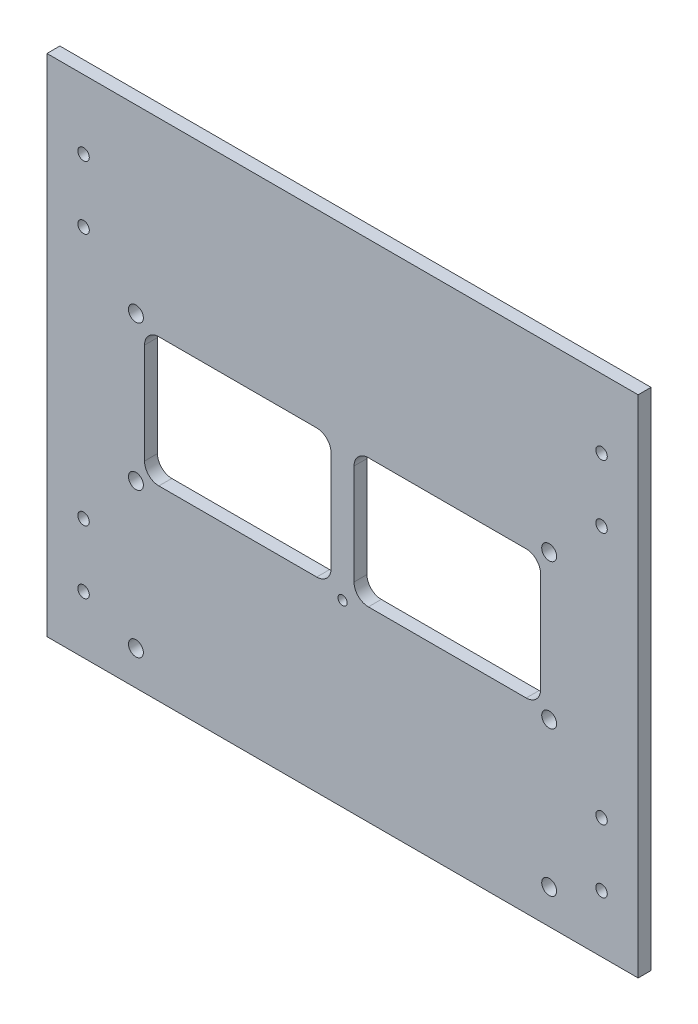
SolidWorks part; units mm, degrees
material "ABS PC"
ref_plane "前视基准面" through (0, 0, 0) normal (0, 0, 1) x (1, 0, 0)
ref_plane "上视基准面" through (0, 0, 0) normal (0, 1, 0) x (1, 0, 0)
ref_plane "右视基准面" through (0, 0, 0) normal (1, 0, 0) x (0, 0, -1)
sketch "草图1" plane through (0, 0, 0) normal (0, 0, 1) x (1, 0, 0)
  line L1 (0, 0) -> (206, 0)
  line L2 (0, 0) -> (0, 176)
  line L3 (0, 176) -> (206, 176)
  line L4 (206, 0) -> (206, 176)
  dimension "D1" = 176
  dimension "D2" = 206
extrude "凸台-拉伸1" add sketch "草图1" along normal blind 4.5
sketch "草图2" plane through (0, 0, 4.5) normal (0, 0, 1) x (1, 0, 0)
  line L0 (103, 0) -> (103, 176) construction
  line L1 (0, 0) -> (206, 0) construction
  line L2 (206, 176) -> (0, 176) construction
  line L3 (12.75, -17.1088) -> (12.75, 176) construction
  line L4 (0, 176) -> (0, 0) construction
  line L5 (193.25, -17.1088) -> (193.25, 176) construction
  circle A0 centre (12.75, 152) radius 2
  circle A1 centre (12.75, 130) radius 2
  circle A2 centre (12.75, 42) radius 2
  circle A3 centre (12.75, 20) radius 2
  circle A4 centre (193.25, 20) radius 2
  circle A5 centre (193.25, 42) radius 2
  circle A6 centre (193.25, 130) radius 2
  circle A7 centre (193.25, 152) radius 2
  dimension "D1" = 4
  dimension "D2" = 22
  dimension "D3" = 22
  dimension "D4" = 20
  dimension "D5" = 110
  dimension "D6" = 12.75
extrude "切除-拉伸1" cut sketch "草图2" against normal up to next
sketch "草图3" plane through (0, 0, 4.5) normal (0, 0, 1) x (1, 0, 0)
  line L1 (103, 176) -> (103, 0) construction
  line L2 (206, 176) -> (0, 176) construction
  line L3 (0, 0) -> (206, 0) construction
  line L51 (167, 65) -> (112, 65)
  line L57 (31, 12) -> (175, 12) construction
  line L58 (31, 12) -> (31, 113) construction
  line L59 (31, 113) -> (175, 113) construction
  line L60 (175, 12) -> (175, 113) construction
  line L61 (31, 12) -> (175, 113) construction
  line L62 (31, 113) -> (175, 12) construction
  line L63 (39, 110) -> (94, 110)
  line L64 (34, 105) -> (34, 70)
  line L65 (39, 65) -> (94, 65)
  line L66 (99, 105) -> (99, 70)
  line L67 (107, 105) -> (107, 70)
  line L68 (167, 110) -> (112, 110)
  line L69 (172, 105) -> (172, 70)
  arc A24 (34, 70) -> (39, 65) centre (39, 70) ccw
  arc A25 (94, 65) -> (99, 70) centre (94, 70) ccw
  arc A26 (94, 110) -> (99, 105) centre (94, 105) cw
  arc A27 (39, 110) -> (34, 105) centre (39, 105) ccw
  arc A28 (172, 70) -> (167, 65) centre (167, 70) cw
  arc A29 (112, 65) -> (107, 70) centre (112, 70) cw
  arc A30 (112, 110) -> (107, 105) centre (112, 105) ccw
  arc A31 (167, 110) -> (172, 105) centre (167, 105) cw
  circle A32 centre (31, 113) radius 2.6
  circle A33 centre (31, 62.5) radius 2.6
  circle A34 centre (31, 12) radius 2.6
  circle A35 centre (175, 12) radius 2.6
  circle A36 centre (175, 62.5) radius 2.6
  circle A37 centre (175, 113) radius 2.6
  circle A38 centre (103, 62.5) radius 1.6
  point P7 (103, 62.5)
  point P17 (34, 65)
  point P22 (99, 110)
  point P25 (34, 110)
  dimension "D5" = 3
  dimension "D10" = 3.2
  dimension "D8" = 5
  dimension "D9" = 5.2
  dimension "D1" = 4
  dimension "D2" = 65
  dimension "D3" = 45
  dimension "D4" = 65
  dimension "D6" = 3
  dimension "D7" = 101
extrude "切除-拉伸2" cut sketch "草图3" against normal up to next
